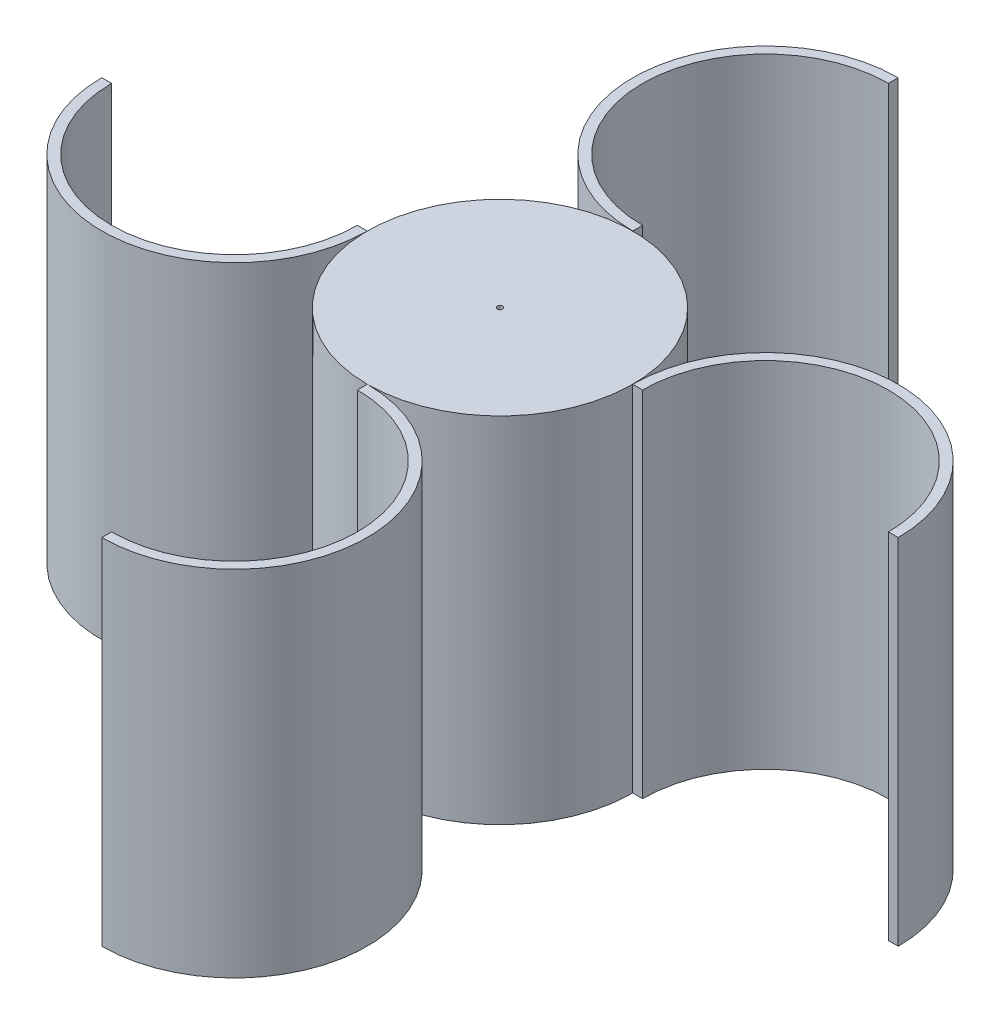
SolidWorks part; units mm, degrees
ref_plane "Front Plane" through (0, 0, 0) normal (0, 0, 1) x (1, 0, 0)
ref_plane "Top Plane" through (0, 0, 0) normal (0, 1, 0) x (1, 0, 0)
ref_plane "Right Plane" through (0, 0, 0) normal (1, 0, 0) x (0, 0, -1)
sketch "Sketch1" plane through (0, 0, 0) normal (0, 1, 0) x (1, 0, 0)
  circle A0 centre (0, 0) radius 7.5
  dimension "D1" = 15
extrude "Boss-Extrude1" add sketch "Sketch1" along normal blind 20
sketch "Sketch2" plane through (0, 0, 0) normal (0, -1, 0) x (1, 0, 0)
  circle A0 centre (0, 0) radius 0.15
  dimension "D1" = 0.3
extrude "Cut-Extrude2" cut sketch "Sketch2" against normal blind 20
sketch "Sketch4" plane through (0, 20, 0) normal (0, 1, 0) x (1, 0, 0)
  line L0 (0, 22.5) -> (0, 21.9458)
  line L1 (0, 8.0542) -> (0, 7.5)
  line L2 (8.0542, 0) -> (7.5, 0)
  line L3 (22.5, 0) -> (21.9458, 0)
  line L4 (0, -8.0542) -> (0, -7.5)
  line L5 (0, -22.5) -> (0, -21.9458)
  line L6 (-8.0542, 0) -> (-7.5, 0)
  line L7 (-22.5, 0) -> (-21.9458, 0)
  circle A0 centre (0, 0) radius 15
  arc A1 (0, 22.5) -> (0, 7.5) centre (0, 15) ccw
  arc A2 (0, 21.9458) -> (0, 8.0542) centre (0, 15) ccw
  arc A3 (22.5, 0) -> (7.5, 0) centre (15, 0) ccw
  arc A4 (21.9458, 0) -> (8.0542, 0) centre (15, 0) ccw
  arc A5 (0, -22.5) -> (0, -7.5) centre (0, -15) ccw
  arc A6 (0, -21.9458) -> (0, -8.0542) centre (0, -15) ccw
  arc A7 (-22.5, 0) -> (-7.5, 0) centre (-15, 0) ccw
  arc A8 (-21.9458, 0) -> (-8.0542, 0) centre (-15, 0) ccw
  point P26 (0, 0)
  dimension "D1" = 30
  dimension "D2" = 4
extrude "Boss-Extrude3" add sketch "Sketch4" against normal blind 20 separate body contours A2 L0 A1 A0 | A2 A0 A1 L1 | A8 A0 A7 L6 | A8 L7 A7 A0 | A6 A0 A5 L4 | A6 L5 A5 A0 | A4 A0 A3 L2 | A4 L3 A3 A0
